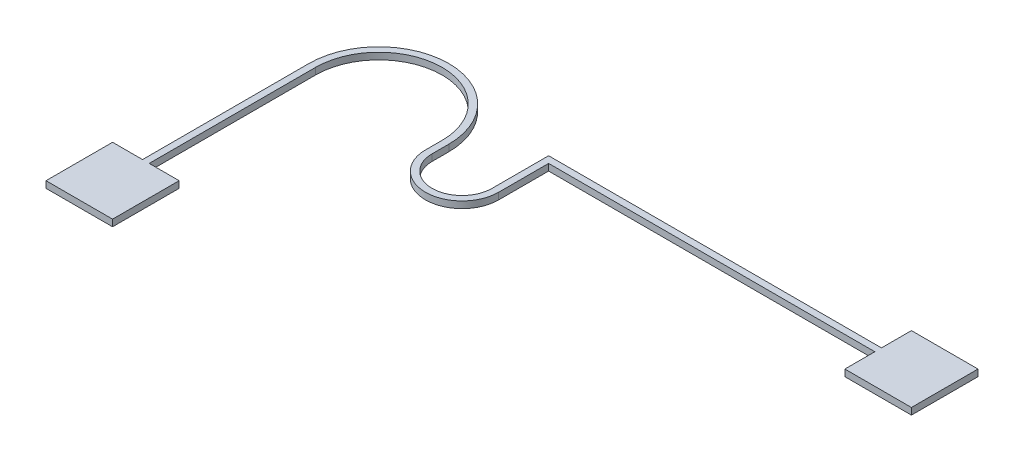
SolidWorks part; units mm, degrees
ref_plane "Front Plane" through (0, 0, 0) normal (0, 0, 1) x (1, 0, 0)
ref_plane "Top Plane" through (0, 0, 0) normal (0, 1, 0) x (1, 0, 0)
ref_plane "Right Plane" through (0, 0, 0) normal (1, 0, 0) x (0, 0, -1)
sketch "Sketch1" plane through (0, 0, 0) normal (0, 1, 0) x (1, 0, 0)
  line L1 (-100, 100) -> (100, 100)
  line L2 (-100, 100) -> (-100, -100)
  line L3 (-100, -100) -> (100, -100)
  line L4 (100, 100) -> (100, -100)
  line L5 (0, -100) -> (0, 100) construction
  line L6 (-100, 0) -> (100, 0) construction
  line L7 (-10, 600) -> (10, 600)
  line L8 (-10, 600) -> (-10, 100)
  line L9 (-10, 100) -> (10, 100)
  line L10 (10, 600) -> (10, 100)
  line L11 (0, 100) -> (0, 600) construction
  line L12 (-10, 350) -> (10, 350) construction
  line L13 (390, 550) -> (410, 550)
  line L14 (390, 550) -> (390, 600)
  line L15 (390, 600) -> (410, 600)
  line L16 (410, 550) -> (410, 600)
  line L17 (590, 600) -> (610, 600)
  line L18 (590, 600) -> (590, 550)
  line L19 (590, 550) -> (610, 550)
  line L20 (610, 600) -> (610, 550)
  line L21 (610, 600) -> (590, 600)
  line L22 (610, 600) -> (610, 700)
  line L23 (610, 700) -> (590, 700)
  line L24 (590, 600) -> (590, 700)
  line L25 (1590, 720) -> (590, 720)
  line L26 (1590, 720) -> (1590, 700)
  line L27 (1590, 700) -> (590, 700)
  line L28 (590, 720) -> (590, 700)
  line L29 (1090, 700) -> (1090, 720) construction
  line L30 (1590, 710) -> (590, 710) construction
  line L31 (1590, 810) -> (1790, 810)
  line L32 (1590, 810) -> (1590, 610)
  line L33 (1590, 610) -> (1790, 610)
  line L34 (1790, 810) -> (1790, 610)
  line L35 (1690, 610) -> (1690, 810) construction
  line L36 (1590, 710) -> (1790, 710) construction
  arc A0 (-10, 600) -> (410, 600) centre (200, 600) cw
  arc A1 (10, 600) -> (390, 600) centre (200, 600) cw
  arc A2 (410, 550) -> (590, 550) centre (500, 550) ccw
  arc A3 (390, 550) -> (610, 550) centre (500, 550) ccw
  point P0 (0, 0)
  point P4 (0, 350)
  point P29 (1090, 710)
  point P30 (1690, 710)
  dimension "D9" = 50
  dimension "D12" = 100
  dimension "D1" = 200
  dimension "D2" = 200
  dimension "D3" = 500
  dimension "D4" = 20
  dimension "D5" = 50
  dimension "D6" = 20
  dimension "D7" = 380
  dimension "D8" = 450
  dimension "D10" = 20
  dimension "D11" = 180
  dimension "D13" = 20
  dimension "D14" = 20
  dimension "D15" = 1000
  dimension "D16" = 200
  dimension "D17" = 200
  dimension "D18" = 100
extrude "Boss-Extrude1" add sketch "Sketch1" along normal blind 20 contours L4 L1 L2 L3 | L10 L7 L8 L1 | L7 A1 L15 A0 | L13 L16 L15 L14 | L13 A3 L19 A2 | L20 L17 L18 L19 | L24 L17 L22 L23 | L25 L28 L23 L27 L26 | L34 L31 L32 L26 L33
